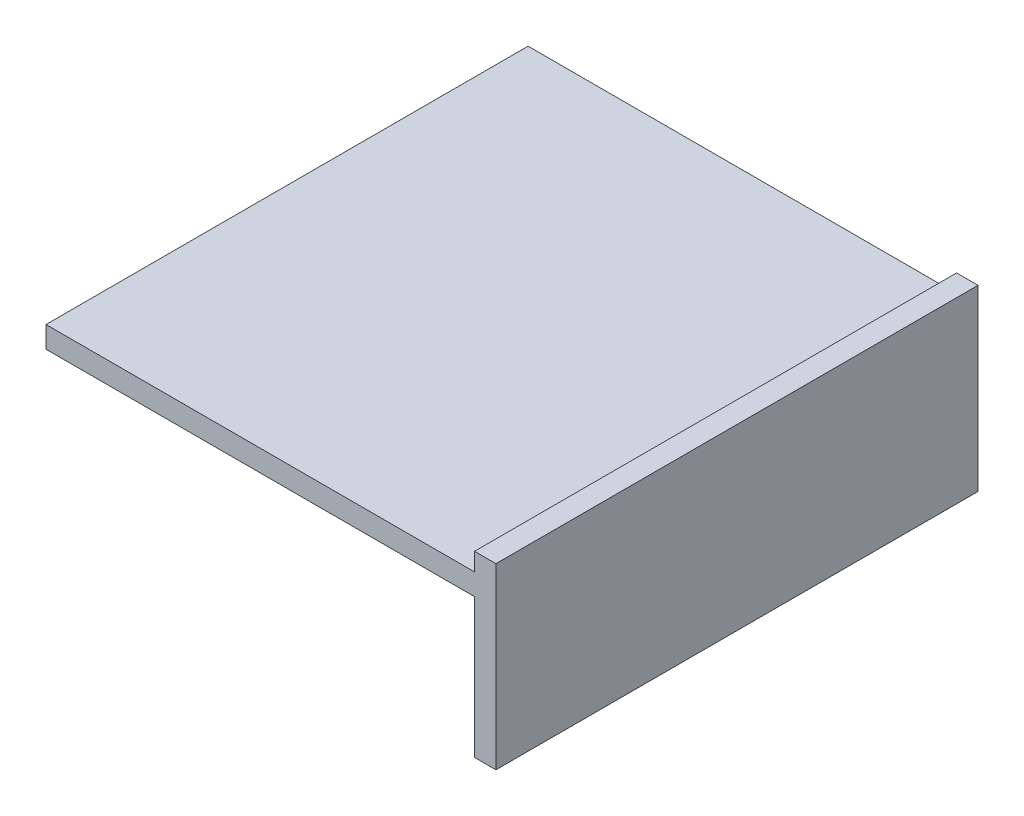
SolidWorks part; units mm, degrees
ref_plane "前视基准面" through (0, 0, 0) normal (0, 0, 1) x (1, 0, 0)
ref_plane "上视基准面" through (0, 0, 0) normal (0, 1, 0) x (1, 0, 0)
ref_plane "右视基准面" through (0, 0, 0) normal (1, 0, 0) x (0, 0, -1)
sketch "草图2" plane through (0, 0, 0) normal (0, 1, 0) x (1, 0, 0)
  line L1 (0, 0) -> (240, 0)
  line L2 (0, 0) -> (0, 270)
  line L3 (0, 270) -> (240, 270)
  line L4 (240, 0) -> (240, 270)
  dimension "D1" = 240
  dimension "D2" = 270
extrude "凸台-拉伸1" add sketch "草图2" along normal blind 12
sketch "草图3" plane through (240, 0, 0) normal (1, 0, 0) x (0, 0, -1)
  line L1 (270, 22) -> (0, 22)
  line L2 (270, 22) -> (270, -78)
  line L3 (270, -78) -> (0, -78)
  line L4 (0, 22) -> (0, -78)
  line L5 (0, 12) -> (270, 12) construction
  line L6 (0, 12) -> (0, 0) construction
  line L7 (270, 12) -> (270, 0) construction
  dimension "D1" = 100
  dimension "D2" = 10
extrude "凸台-拉伸2" add sketch "草图3" along normal blind 12
sketch "草图4" plane through (240, 0, 0) normal (-1, 0, 0) x (0, 0, 1)
  line L0 (0, 0) -> (-270, 0) construction
  line L1 (-270, -78) -> (-258, -78)
  line L2 (-270, -78) -> (-270, 0)
  line L3 (-270, 0) -> (-258, 0)
  line L4 (-258, -78) -> (-258, 0)
  dimension "D1" = 12
extrude "凸台-拉伸3" add sketch "草图4" along normal blind 240
